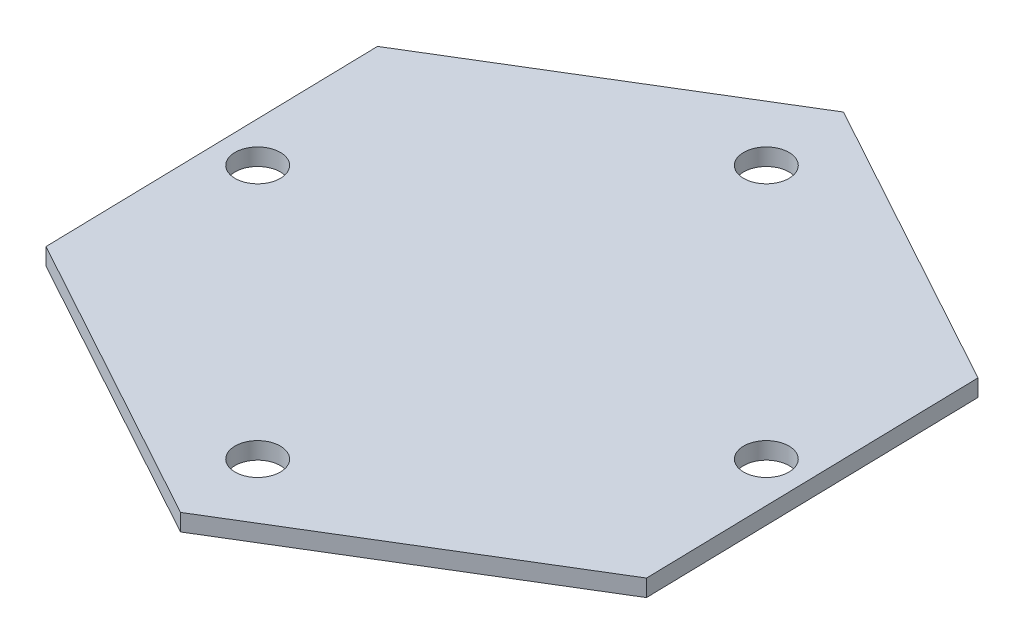
SolidWorks part; units mm, degrees
material "6061-T6 (SS)"
ref_plane "Front Plane" through (0, 0, 0) normal (0, 0, 1) x (1, 0, 0)
ref_plane "Top Plane" through (0, 0, 0) normal (0, 1, 0) x (1, 0, 0)
ref_plane "Right Plane" through (0, 0, 0) normal (1, 0, 0) x (0, 0, -1)
sketch "Sketch2" plane through (0, 0, 0) normal (0, 1, 0) x (1, 0, 0)
  line L1 (52.6339, -28.8353) -> (51.2891, 31.1647)
  line L2 (51.2891, 31.1647) -> (-1.3448, 60)
  line L3 (-1.3448, 60) -> (-52.6339, 28.8353)
  line L4 (-52.6339, 28.8353) -> (-51.2891, -31.1647)
  line L5 (-51.2891, -31.1647) -> (1.3448, -60)
  line L6 (1.3448, -60) -> (52.6339, -28.8353)
  circle A0 centre (0, 0) radius 51.9746 construction
  dimension "D1" = 60
extrude "Boss-Extrude1" add sketch "Sketch2" along normal blind 3 contours L4 L5 L6 L1 L2 L3
sketch "Sketch3" plane through (0, 3, 0) normal (0, 1, 0) x (1, 0, 0)
  circle A4 centre (-45, 0) radius 4
  circle A5 centre (0, 45) radius 4
  circle A6 centre (45, 0) radius 4
  circle A7 centre (0, -45) radius 4
  dimension "D2" = 8
extrude "Cut-Extrude1" cut sketch "Sketch3" against normal through all contours A4 | A5 | A6 | A7
